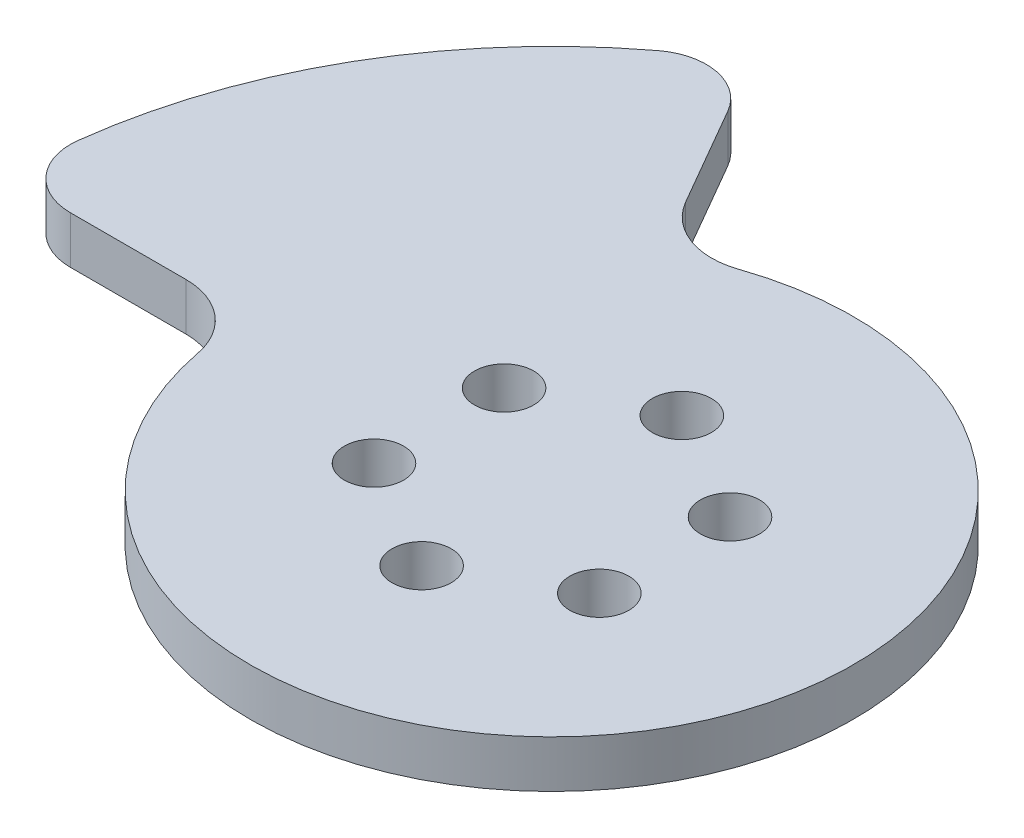
SolidWorks part; units mm, degrees
ref_plane "前视基准面" through (0, 0, 0) normal (0, 0, 1) x (1, 0, 0)
ref_plane "上视基准面" through (0, 0, 0) normal (0, 1, 0) x (1, 0, 0)
ref_plane "右视基准面" through (0, 0, 0) normal (1, 0, 0) x (0, 0, -1)
sketch "草图1" plane through (0, 0, 0) normal (0, 1, 0) x (1, 0, 0)
  line L0 (-20.347, 35.242) -> (-15.4616, 26.7804)
  line L1 (-30.9233, 0) -> (-40.694, 0)
  line L3 (0, -11) -> (9.5263, -5.5) construction
  line L4 (9.5263, -5.5) -> (9.5263, 5.5) construction
  line L5 (9.5263, 5.5) -> (0, 11) construction
  line L6 (0, 11) -> (-9.5263, 5.5) construction
  line L7 (-9.5263, 5.5) -> (-9.5263, -5.5) construction
  line L8 (-9.5263, -5.5) -> (0, -11) construction
  circle A0 centre (0, 0) radius 25.5 construction
  circle A1 centre (0, 0) radius 46 construction
  arc A2 (-8.3102, 24.1079) -> (-25.0331, -4.8571) centre (0, 0) cw
  arc A3 (-27.6865, 36.7349) -> (-45.6567, 5.6098) centre (0, 0) ccw
  arc A4 (-25.0331, -4.8571) -> (-30.9233, 0) centre (-30.9233, -6) ccw
  arc A5 (-8.3102, 24.1079) -> (-15.4616, 26.7804) centre (-10.2655, 29.7804) cw
  arc A6 (-45.6567, 5.6098) -> (-40.694, 0) centre (-40.694, 5) ccw
  arc A7 (-27.6865, 36.7349) -> (-20.347, 35.242) centre (-24.6771, 32.742) cw
  circle A8 centre (0, 0) radius 11 construction
  circle A9 centre (0, 0) radius 9.5263 construction
  circle A10 centre (0, 11) radius 2.5
  circle A11 centre (9.4621, 5.6098) radius 2.5
  circle A12 centre (9.5263, -5.5) radius 2.5
  circle A13 centre (0, -11) radius 2.5
  circle A14 centre (-9.5263, -5.5) radius 2.5
  circle A15 centre (-9.5263, 5.5) radius 2.5
  point P14 (-25.5, 0)
  point P17 (-12.75, 22.0836)
  point P20 (-46, 0)
  point P23 (-23, 39.8372)
  dimension "D1" = 51
  dimension "D2" = 92
  dimension "D3" = 6
  dimension "D4" = 5
  dimension "D6" = 22
  dimension "D7" = 5
  dimension "D5" = 60
extrude "凸台-拉伸1" add sketch "草图1" along normal blind 4
